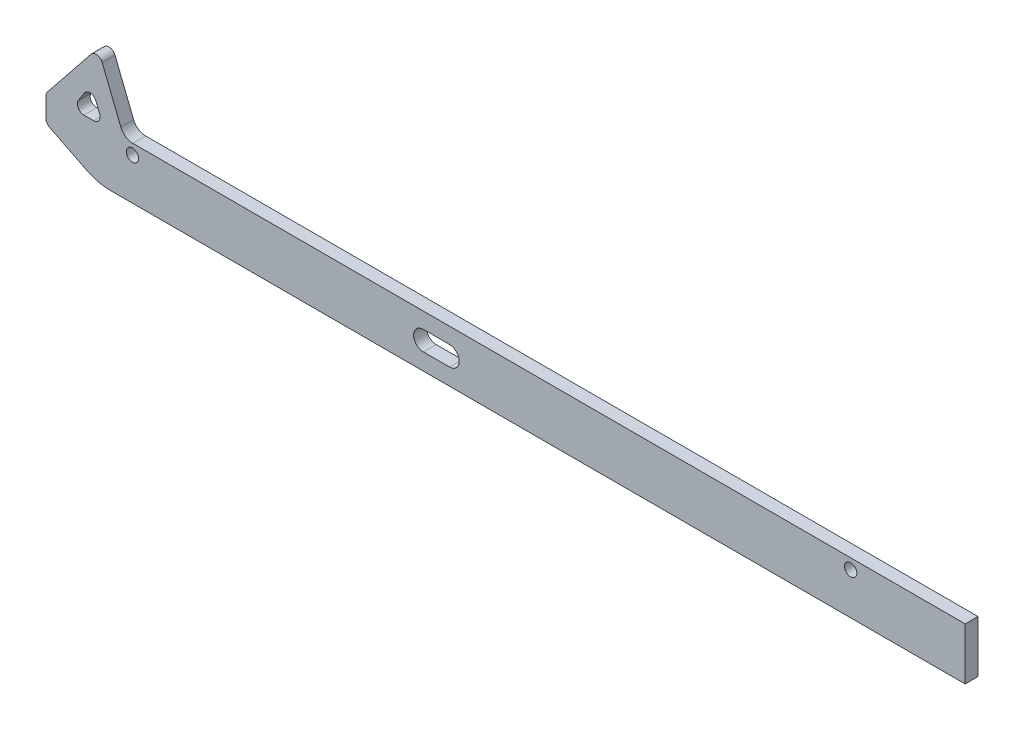
SolidWorks part; units mm, degrees
ref_plane "Front Plane" through (0, 0, 0) normal (0, 0, 1) x (1, 0, 0)
ref_plane "Top Plane" through (0, 0, 0) normal (0, 1, 0) x (1, 0, 0)
ref_plane "Right Plane" through (0, 0, 0) normal (1, 0, 0) x (0, 0, -1)
sketch "Sketch1" plane through (0, 0, 0) normal (0, 0, 1) x (1, 0, 0)
  line L0 (-110.4919, 6.2563) -> (-110.4919, 38.0063) construction
  line L1 (113.7998, -6.4437) -> (-97.7919, -6.4437)
  line L2 (113.7998, -6.4437) -> (113.7998, 6.2563)
  line L3 (113.7998, 6.2563) -> (-91.4419, 6.2563)
  line L4 (-97.7919, 22.1313) -> (-110.4919, 6.2563)
  line L5 (113.7998, -6.4437) -> (-110.4919, 6.2563) construction
  line L6 (113.7998, 6.2563) -> (-117.2068, -6.4437) construction
  line L7 (-110.4919, 38.0063) -> (-104.1419, 38.0063) construction
  line L8 (-110.4919, -0.0937) -> (-97.7919, -6.4437)
  line L9 (-104.1419, 38.0063) -> (-97.7919, 22.1313) construction
  line L10 (-104.1419, 6.2563) -> (-104.1419, 25.3063) construction
  line L11 (-104.1419, 25.3063) -> (-96.5219, 6.2563) construction
  line L12 (-104.1419, 6.2563) -> (-100.3319, 15.7813) construction
  line L13 (-100.3319, 15.7813) -> (-97.7919, 22.1313) construction
  line L14 (-110.4919, 6.2563) -> (-110.4919, -0.0937)
  line L15 (-97.7919, 22.1313) -> (-91.4419, 6.2563)
  line L16 (-104.1419, 6.2563) -> (-99.4608, 13.6034)
  line L17 (-99.4608, 13.6034) -> (-96.5219, 6.2563)
  line L18 (-96.5219, 6.2563) -> (-104.1419, 6.2563)
  line L19 (-97.7919, 22.1313) -> (-91.4419, 6.2563) construction
  point P0 (0, 0)
  dimension "D1" = 6.35
  dimension "D2" = 224.2918
  dimension "D3" = 6.35
  dimension "D4" = 12.7
  dimension "D5" = 31.75
  dimension "D6" = 19.05
  dimension "D7" = 6.35
  dimension "D9" = 12.7
extrude "Boss-Extrude1" add sketch "Sketch1" along normal blind 3.1242
fillet "Fillet4" radius 12.7 1 edges at (-97.7919, -6.4437, 1.5621)
fillet "Fillet8" radius 1.5875 6 edges at (-110.4919, -0.0937, 1.5621) (-110.4919, 6.2563, 1.5621) (-97.7919, 22.1313, 1.5621) (-99.4608, 13.6034, 1.5621) (-104.1419, 6.2563, 1.5621) (-96.5219, 6.2563, 1.5621)
fillet "Fillet9" radius 3.175 1 edges at (-91.4419, 6.2563, 1.5621)
sketch "Sketch2" plane through (0, 0, 3.1242) normal (0, 0, 1) x (1, 0, 0)
  line L0 (-18.4072, 0) -> (-12.0572, 0) construction
  line L1 (-18.4072, 2.3813) -> (-12.0572, 2.3813)
  line L2 (-18.4072, -2.3813) -> (-12.0572, -2.3813)
  line L4 (113.7998, -6.4437) -> (113.7998, 6.2563) construction
  arc A0 (-18.4072, 2.3813) -> (-18.4072, -2.3813) centre (-18.4072, 0) ccw
  arc A1 (-12.0572, -2.3813) -> (-12.0572, 2.3813) centre (-12.0572, 0) ccw
  point P3 (-15.2322, 0)
  point P8 (113.7998, -0.0937)
  dimension "D2" = 2.3813
  dimension "D1" = 6.35
  dimension "D3" = 129.032
extrude "Cut-Extrude1" cut sketch "Sketch2" against normal through all
sketch "Sketch3" plane through (0, 0, 3.1242) normal (0, 0, 1) x (1, 0, 0)
  line L0 (113.7998, 3.7163) -> (0, 3.7163) construction
  line L2 (-94.7939, -6.4437) -> (113.7998, -6.4437) construction
  line L3 (113.7998, -6.4437) -> (113.7998, 6.2563) construction
  circle A0 centre (85.8598, 3.7163) radius 1.5
  circle A1 centre (-89.4002, 3.7163) radius 1.5
  dimension "D1" = 3
  dimension "D4" = 3
  dimension "D2" = 27.94
  dimension "D3" = 10.16
  dimension "D5" = 203.2
extrude "Cut-Extrude2" cut sketch "Sketch3" against normal through all
